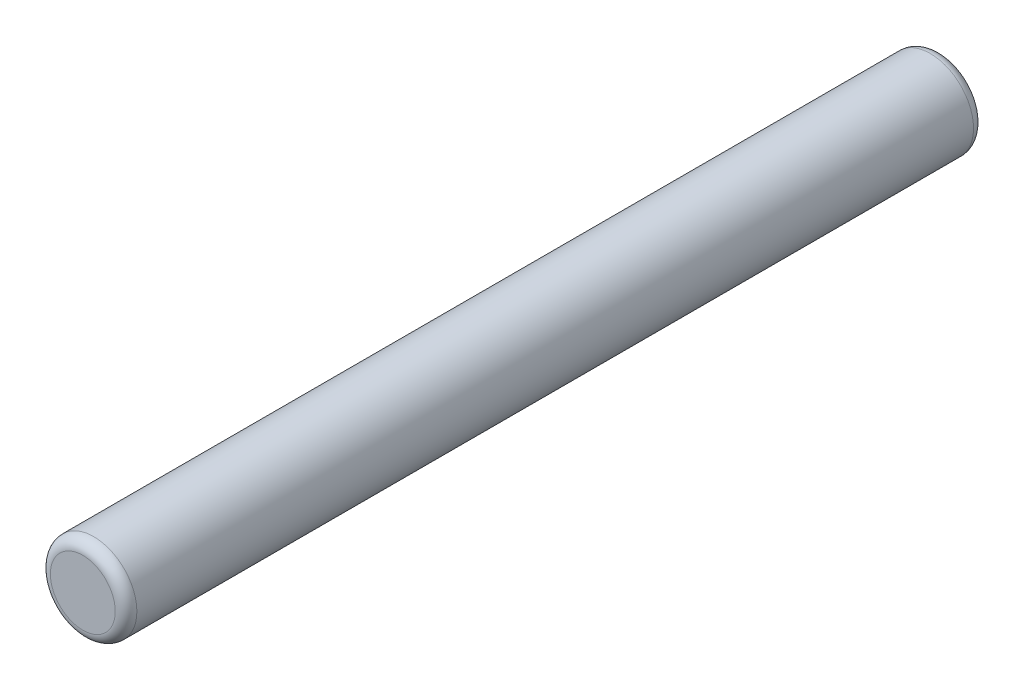
SolidWorks part; units mm, degrees
ref_plane "Plan1" through (0, 0, 0) normal (0, 0, 1) x (1, 0, 0)
ref_plane "Plan2" through (0, 0, 0) normal (0, 1, 0) x (1, 0, 0)
ref_plane "Plan3" through (0, 0, 0) normal (1, 0, 0) x (0, 0, -1)
sketch "Esquisse1" plane through (0, 0, 0) normal (0, 0, 1) x (1, 0, 0)
  circle A0 centre (0, 0) radius 2
  dimension "D1" = 4
extrude "Base-Extrusion" add sketch "Esquisse1" along normal mid plane 39.7
fillet "Congé1" radius 0.5
